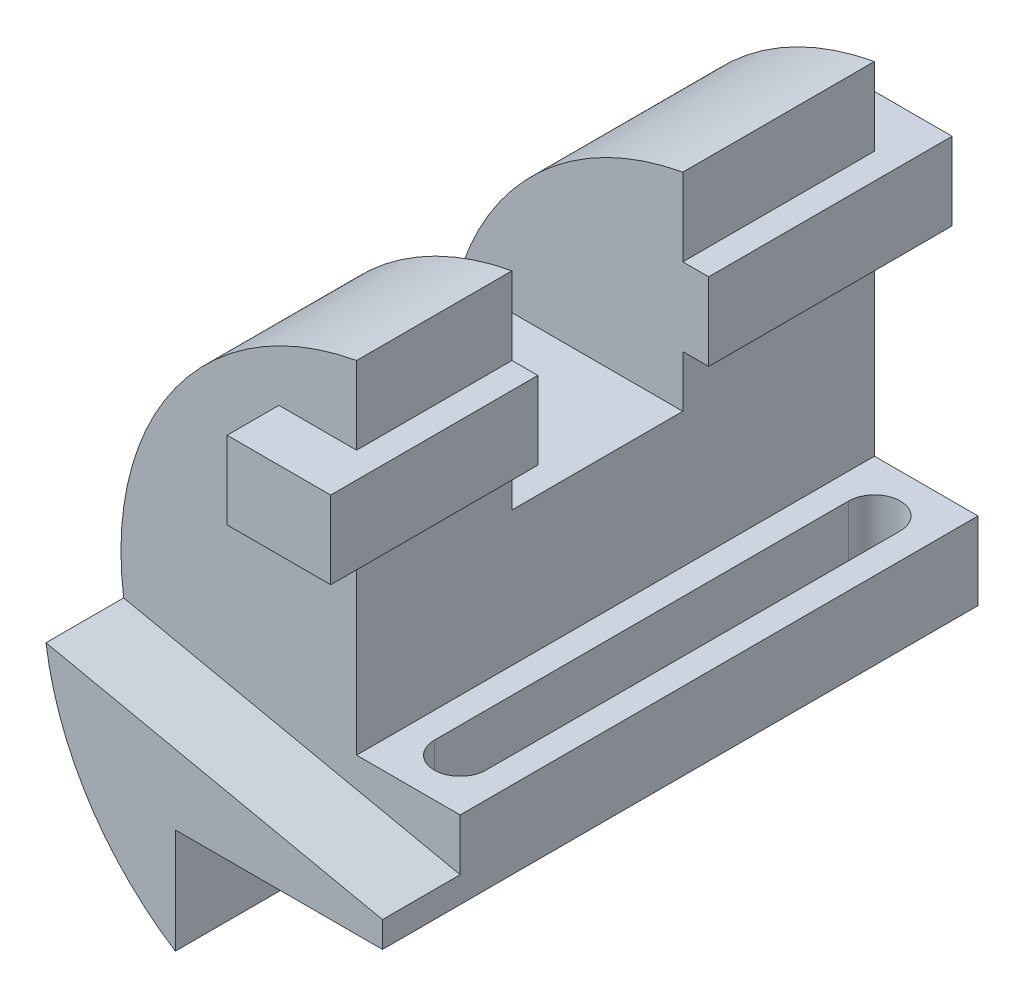
SolidWorks part; units mm, degrees
material "1060 Alloy"
ref_plane "Front Plane" through (0, 0, 0) normal (0, 0, 1) x (1, 0, 0)
ref_plane "Top Plane" through (0, 0, 0) normal (0, 1, 0) x (1, 0, 0)
ref_plane "Right Plane" through (0, 0, 0) normal (1, 0, 0) x (0, 0, -1)
sketch "Sketch1" plane through (0, 0, 0) normal (0, 0, 1) x (1, 0, 0)
  line L0 (0, 0) -> (-40, 0)
  line L1 (-40, 0) -> (-40, -20.2848)
  line L3 (0, 15) -> (-20, 15)
  line L4 (-20, 15) -> (-20, 81)
  line L5 (0, 0) -> (0, 15)
  arc A0 (-40, -20.2848) -> (-20, 81) centre (-10, 26.4083) cw
  dimension "D5" = 55.5
  dimension "D1" = 40
  dimension "D2" = 15
  dimension "D3" = 20
  dimension "D4" = 10
  dimension "D6" = 66
extrude "Boss-Extrude1" add sketch "Sketch1" along normal blind 115
sketch "Sketch2" plane through (0, 0, 115) normal (0, 0, 1) x (1, 0, 0)
  line L0 (0, 5) -> (-64.9776, 18.8114)
  line L1 (0, 0) -> (0, 15) construction
  line L7 (0, 0) -> (0, 15)
  line L8 (0, 15) -> (-20, 15)
  line L9 (-20, 15) -> (-20, 81)
  line L10 (-40, -20.2848) -> (-40, 0)
  line L11 (-40, 0) -> (0, 0)
  line L12 (0, 5) -> (0, 15)
  line L13 (0, 15) -> (-20, 15)
  line L14 (-20, 15) -> (-20, 81)
  arc A0 (-20, 81) -> (-40, -20.2848) centre (-10, 26.4083) ccw construction
  arc A2 (-20, 81) -> (-40, -20.2848) centre (-10, 26.4083) ccw
  arc A3 (-20, 81) -> (-64.9776, 18.8114) centre (-10, 26.4083) ccw
  dimension "D1" = 5
  dimension "D3" = 78
  dimension "D2" = 0
extrude "Cut-Extrude1" cut sketch "Sketch2" against normal blind 15 contours L12 L13 L14 A3 L0
sketch "Sketch3" plane through (0, 0, 0) normal (0, 0, -1) x (-1, 0, 0)
  line L0 (20, 15) -> (20, 81) construction
  line L1 (15, 66) -> (35, 66)
  line L2 (15, 66) -> (15, 51)
  line L3 (15, 51) -> (35, 51)
  line L4 (35, 66) -> (35, 51)
  dimension "D1" = 5
  dimension "D2" = 20
  dimension "D3" = 15
  dimension "D4" = 15
extrude "Boss-Extrude3" add sketch "Sketch3" against normal offset from surface 5 and the other way blind 10 up to face at (-29.8517, 0.1583, 115)
sketch "Sketch4" plane through (-20, 0, 0) normal (1, 0, 0) x (0, 0, -1)
  line L0 (-100, 81) -> (0, 81) construction
  line L1 (10, 51) -> (-110, 51) construction
  line L2 (-70, 81) -> (-37, 81)
  line L3 (-70, 81) -> (-70, 41)
  line L4 (-70, 41) -> (-37, 41)
  line L5 (-37, 81) -> (-37, 41)
  dimension "D1" = 30
  dimension "D2" = 33
  dimension "D3" = 10
extrude "Cut-Extrude3" cut sketch "Sketch4" against normal through all both and the other way through all
sketch "Sketch5" plane through (0, 15, 0) normal (0, 1, 0) x (1, 0, 0)
  line L0 (-10, -10) -> (-10, -90) construction
  line L1 (-5, -10) -> (-5, -90)
  line L2 (-15, -10) -> (-15, -90)
  line L3 (0, -100) -> (-64.9776, -100) construction
  line L4 (0, -100) -> (0, 0) construction
  arc A0 (-5, -10) -> (-15, -10) centre (-10, -10) ccw
  arc A1 (-15, -90) -> (-5, -90) centre (-10, -90) ccw
  point P2 (-10, -50)
  dimension "D1" = 80
  dimension "D2" = 10
  dimension "D3" = 10
  dimension "D4" = 10
extrude "Cut-Extrude4" cut sketch "Sketch5" against normal through all and the other way through all contours L2 A1 L1 A0
equation "\"a\"= 55.5mm"
equation "\"b\"= 66mm"
equation "\"c\"= 33mm"
equation "\"D5@Sketch1\"=\"a\""
equation "\"D6@Sketch1\"=\"b\""
equation "\"D2@Sketch4\"=\"c\""
